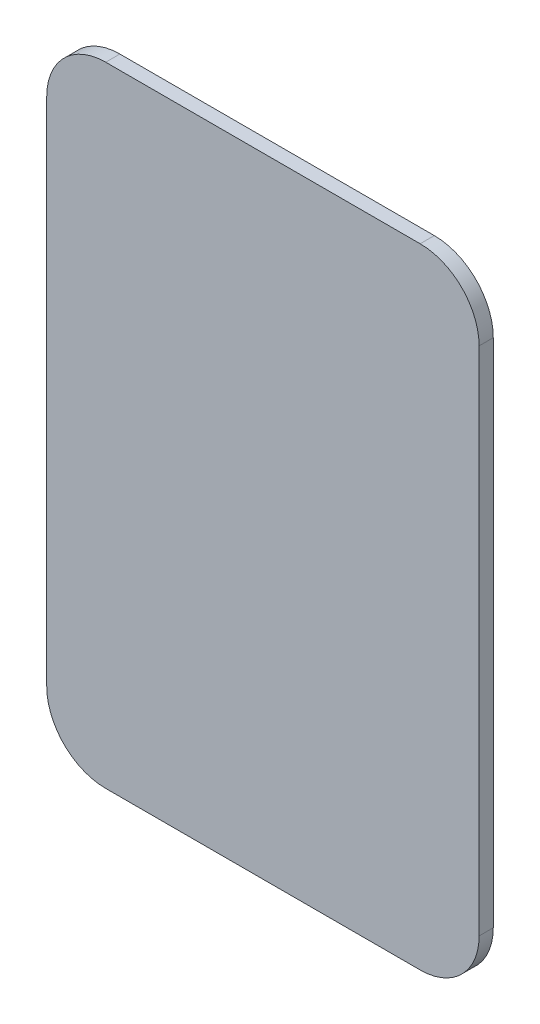
SolidWorks part; units mm, degrees
ref_plane "Front Plane" through (0, 0, 0) normal (0, 0, 1) x (1, 0, 0)
ref_plane "Top Plane" through (0, 0, 0) normal (0, 1, 0) x (1, 0, 0)
ref_plane "Right Plane" through (0, 0, 0) normal (1, 0, 0) x (0, 0, -1)
sketch "Model" plane through (0, 0, 0) normal (0, 0, 1) x (1, 0, 0)
  line L30 (177.8, 812.8) -> (584.2, 812.8)
  line L31 (660.4, 889) -> (660.4, 1549.4)
  line L32 (584.2, 1625.6) -> (177.8, 1625.6)
  line L33 (101.6, 1549.4) -> (101.6, 889)
  arc A15 (101.6, 889) -> (177.8, 812.8) centre (177.8, 889) ccw
  arc A16 (584.2, 812.8) -> (660.4, 889) centre (584.2, 889) ccw
  arc A17 (660.4, 1549.4) -> (584.2, 1625.6) centre (584.2, 1549.4) ccw
  arc A18 (177.8, 1625.6) -> (101.6, 1549.4) centre (177.8, 1549.4) ccw
extrude "Boss-Extrude1" add sketch "Model" along normal blind 18.288
